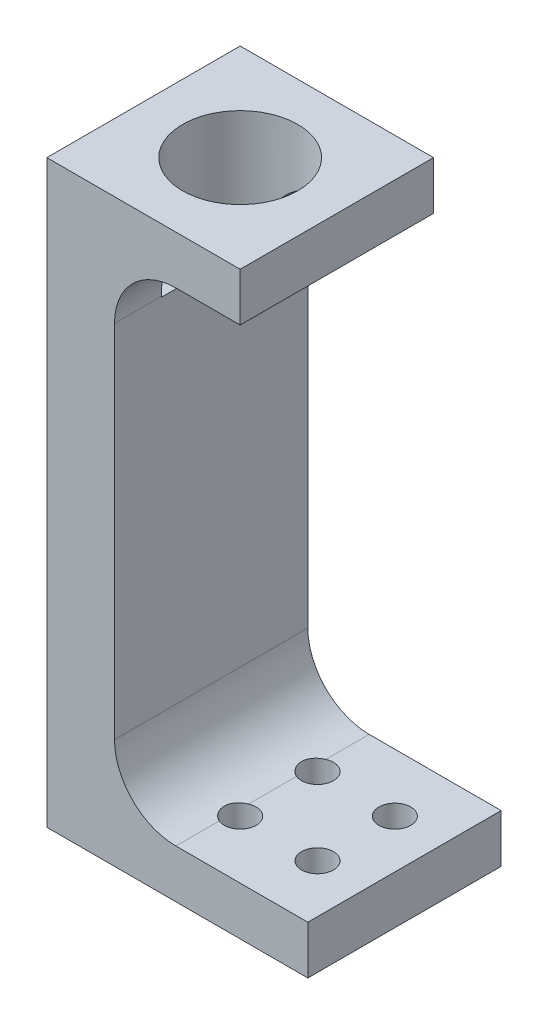
SolidWorks part; units mm, degrees
ref_plane "Front Plane" through (0, 0, 0) normal (0, 0, 1) x (1, 0, 0)
ref_plane "Top Plane" through (0, 0, 0) normal (0, 1, 0) x (1, 0, 0)
ref_plane "Right Plane" through (0, 0, 0) normal (1, 0, 0) x (0, 0, -1)
sketch "Sketch1" plane through (0, 0, 0) normal (0, 0, 1) x (1, 0, 0)
  line L0 (0, 0) -> (27, 0)
  line L1 (27, 0) -> (27, 5)
  line L2 (27, 5) -> (7, 5)
  line L3 (7, 5) -> (7, 55)
  line L4 (7, 55) -> (20, 55)
  line L5 (20, 55) -> (20, 60)
  line L6 (20, 60) -> (0, 60)
  line L7 (0, 60) -> (0, 0)
  dimension "D1" = 5
  dimension "D2" = 7
  dimension "D3" = 50
  dimension "D4" = 20
  dimension "D5" = 20
extrude "Boss-Extrude1" add sketch "Sketch1" along normal blind 20
fillet "Fillet1" radius 6.35 2 edges at (7, 5, 10) (7, 55, 10)
hole_wizard "M4x0.7 Tapped Hole1" positions "Sketch3" profile "Sketch4" tap size "M4x0.7" standard "ANSI Metric"
sketch "Sketch3" plane through (0, 0, 0) normal (0, -1, 0) x (-1, 0, 0)
  line L1 (-14, -6) -> (-22, -6)
  line L2 (-14, -6) -> (-14, -14)
  line L3 (-14, -14) -> (-22, -14)
  line L4 (-22, -6) -> (-22, -14)
  line L5 (-14, -6) -> (-22, -14) construction
  line L6 (-14, -14) -> (-22, -6) construction
  line L7 (-27, -10) -> (0, -10) construction
  line L8 (-27, -20) -> (-27, 0) construction
  line L9 (0, -20) -> (0, 0) construction
  point P0 (-22, -14)
  point P2 (-22, -6)
  point P4 (-14, -6)
  point P6 (-14, -14)
  point P94 (-18, -10)
  dimension "D1" = 8
  dimension "D2" = 5
sketch "Sketch4" plane through (22, 0, 14) normal (1, 0, 0) x (0, 0, -1)
  line L0 (0, 0) -> (0, 11.0914)
  line L1 (0, 11.0914) -> (1.65, 10.1)
  line L2 (1.65, 10.1) -> (1.65, 0)
  line L5 (1.65, 0) -> (0, 0)
  line L10 (0, 11.0914) -> (-1.65, 10.1) construction
  line L11 (0, -6.35) -> (0, 107.95) construction
  dimension "Tap Drill Dia." = 3.3
  dimension "Tap Drill Depth" = 10.1
  dimension "Drill Angle" = 118
cosmetic thread "Hole Thread5"
cosmetic thread "Hole Thread6"
cosmetic thread "Hole Thread7"
cosmetic thread "Hole Thread8"
sketch "Sketch5" plane through (0, 60, 0) normal (0, -1, 0) x (1, 0, 0)
  line L0 (20, 20) -> (0, 0) construction
  circle A0 centre (10, 10) radius 5.9563
  dimension "D1" = 11.9126
extrude "Cut-Extrude1" cut sketch "Sketch5" along normal blind 11.43
